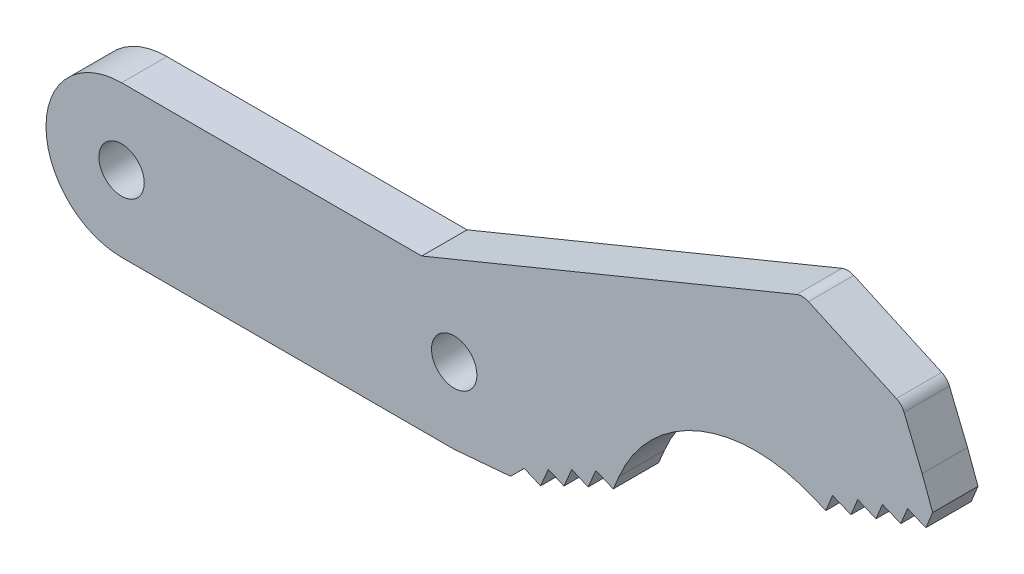
SolidWorks part; units mm, degrees
ref_plane "Front Plane" through (0, 0, 0) normal (0, 0, 1) x (1, 0, 0)
ref_plane "Top Plane" through (0, 0, 0) normal (0, 1, 0) x (1, 0, 0)
ref_plane "Right Plane" through (0, 0, 0) normal (1, 0, 0) x (0, 0, -1)
sketch "Sketch1" plane through (0, 0, 0) normal (0, 0, 1) x (1, 0, 0)
  line L0 (0, 0) -> (22, 0) construction
  line L1 (0, 5) -> (19.85, 5)
  line L2 (0, -5) -> (22, -5)
  line L3 (19.85, 5) -> (44.6431, 15.1937)
  line L4 (45.4379, 15.1788) -> (51.2451, 12.5335)
  line L5 (51.7554, 12.0038) -> (52.955, 9.0863)
  line L10 (46.5818, 3.7797) -> (47.0288, 4.8718)
  line L11 (47.0288, 4.8718) -> (48.2418, 4.3753)
  line L12 (48.2418, 4.3753) -> (48.6888, 5.4674)
  line L13 (48.6888, 5.4674) -> (49.9018, 4.9709)
  line L14 (49.9018, 4.9709) -> (50.3274, 6.0107)
  line L15 (50.3274, 6.0107) -> (51.5404, 5.5142)
  line L16 (51.5404, 5.5142) -> (51.9874, 6.6063)
  line L17 (51.9874, 6.6063) -> (53.2004, 6.1098)
  line L18 (53.2004, 6.1098) -> (53.6474, 7.2018)
  line L19 (53.6474, 7.2018) -> (52.955, 9.0863)
  line L20 (46.5818, 3.7797) -> (45.7368, 4.1256)
  line L24 (27.7149, -4.2379) -> (26.6291, -3.7761)
  line L25 (28.2279, -3.0318) -> (27.7149, -4.2379)
  line L26 (29.2619, -3.4715) -> (28.2279, -3.0318)
  line L27 (29.7748, -2.2654) -> (29.2619, -3.4715)
  line L28 (30.8607, -2.7272) -> (29.7748, -2.2654)
  line L29 (31.3737, -1.5211) -> (30.8607, -2.7272)
  line L30 (32.5211, -2.0091) -> (31.3737, -1.5211)
  line L31 (32.5211, -2.0091) -> (32.9075, -1.1005)
  line L40 (26.6291, -3.7761) -> (25.7291, -4.6794)
  line L41 (22, -5) -> (25.7291, -4.6794)
  arc A0 (0, 5) -> (0, -5) centre (0, 0) ccw
  circle A2 centre (0, 0) radius 1.5
  circle A3 centre (22, 0) radius 1.5
  arc A4 (51.2451, 12.5335) -> (51.7554, 12.0038) centre (50.8306, 11.6235) cw
  arc A5 (44.6431, 15.1937) -> (45.4379, 15.1788) centre (45.0233, 14.2688) cw
  arc A6 (45.7368, 4.1256) -> (32.9075, -1.1005) centre (41.9366, -4.9054) ccw
  point P3 (11, 0)
  point P18 (51.605, 12.3696)
  point P21 (45.0437, 15.3584)
  point P22 (24, -5)
  dimension "D3" = 3
  dimension "D4" = 3
  dimension "D12" = 1
  dimension "D2" = 5
  dimension "D5" = 19.85
  dimension "D6" = 157.65
  dimension "D7" = 27.24
  dimension "D8" = 133.16
  dimension "D9" = 7.21
  dimension "D10" = 136.84
  dimension "D11" = 3.55
  dimension "D13" = 24
  dimension "D14" = 2.9
  dimension "D20" = 1.18
  dimension "D21" = 1.66
  dimension "D22" = 2.0076
  dimension "D23" = 10
  dimension "D24" = 22
extrude "Boss-Extrude1" add sketch "Sketch1" along normal blind 3
